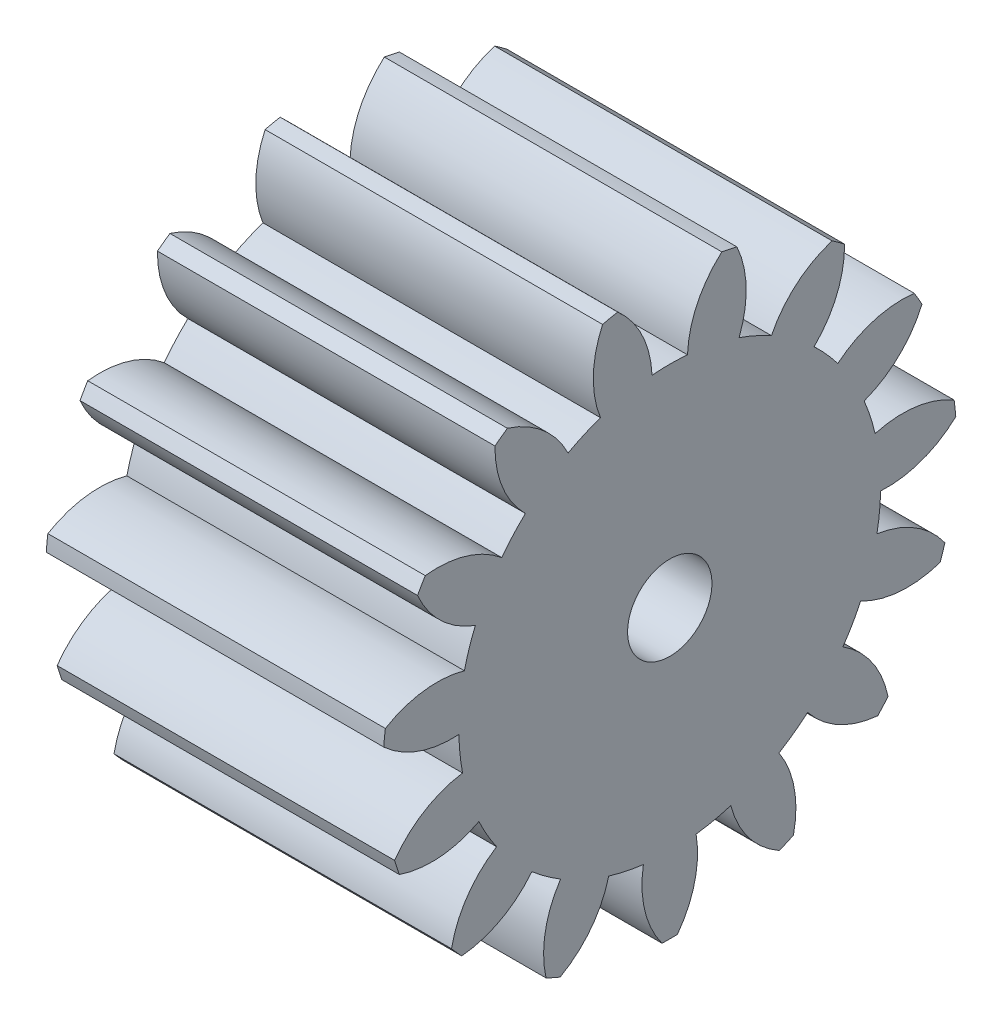
SolidWorks part; units mm, degrees
ref_plane "Plane1" through (0, 0, 0) normal (0, 0, 1) x (1, 0, 0)
ref_plane "Plane2" through (0, 0, 0) normal (0, 1, 0) x (1, 0, 0)
ref_plane "Plane3" through (0, 0, 0) normal (1, 0, 0) x (0, 0, -1)
sketch "HoldingSke" plane through (0, 0, 0) normal (0, 1, 0) x (1, 0, 0)
  line L0 (0, 0) -> (0.483, -0.1294)
  line L1 (-15, 0) -> (100, 0) construction
  line L2 (0, 0) -> (-2.1039, 2.3779)
  line L3 (0, 0) -> (-11.863, 4.5341)
  line L4 (0, 0) -> (8.3417, 2.2352)
  line L5 (0, 0) -> (-46.8476, -17.4728)
  line L6 (0, 0) -> (-16.5793, -11.1861)
  line L7 (-2.1039, 2.3779) -> (8.6586, 51.2059)
  line L8 (-76.2, 54.61) -> (-75.3, 54.61)
  line L9 (-71.009, 38.7566) -> (-53.1078, 45.2721)
  line L10 (-76.2, 71.12) -> (104.1128, 71.12)
  line L11 (0, 0) -> (-20, 0)
  line L12 (-76.2, 101.6) -> (-76.133, 101.6)
  line L13 (24.9733, 27.94) -> (52.9518, 28.4284)
  line L14 (24.9733, 27.94) -> (24.9743, 27.94)
  line L15 (24.9733, 27.94) -> (100.4006, 29.5858)
  line L16 (-63.627, -2) -> (-12.827, -2)
  circle A0 centre (0, 0) radius 2.5
  circle A1 centre (0, 0) radius 12.499
  circle A2 centre (0, 0) radius 37.5
  circle A3 centre (0, 0) radius 2.5
  dimension "MHD" = 24.998
  dimension "Hub_dia" = 75
  dimension "Bore" = 5
  dimension "MBD" = 5
  dimension "Num_teeth" = 15
  dimension "Pitch" = 0.5
  dimension "Overall_len" = 50
  dimension "Show_teeth" = 15
  dimension "Thickness" = 20
  dimension "OAL" = 50.0001
  dimension "T_dim" = 0.9
  dimension "Ap" = 20
  dimension "H" = 19.05
  dimension "Pitch_radius" = 180.3128
  dimension "Width" = 20
  dimension "Backlash" = 0.067
  dimension "Addendum_fac" = 1
  dimension "Dedendum_fac" = 1.25
  dimension "Clearance_fac" = 0.25
  dimension "Dedendum_add" = 0.001
  dimension "Module" = 2
sketch "BasProSke" plane through (0, 0, 0) normal (0, 1, 0) x (1, 0, 0)
  line L0 (-10, 0) -> (60, 0) construction
  line L1 (0, 0) -> (0, 17)
  line L2 (0, 0) -> (20, 0)
  line L3 (20, 0) -> (20, 17)
  line L4 (20, 17) -> (0, 17)
  dimension "Thickness" = 20
  dimension "Diameter" = 34
revolve "Base-Revolve" add sketch "BasProSke" angle 360 about L0
sketch "TooCutSke" plane through (0, 0, 0) normal (1, 0, 0) x (0, 0, -1)
  line L1 (0, 0) -> (0, 107) construction
  line L2 (0, 0) -> (-1.6851, 14.905) construction
  line L3 (0, 0) -> (-6.2081, 29.2069) construction
  line L4 (-1.6851, 14.905) -> (-3.1041, 14.6034) construction
  arc A0 (1.0501, 12.4548) -> (-1.0501, 12.4548) centre (0, 0) ccw
  arc A1 (3.1109, 16.7388) -> (-3.1109, 16.7388) centre (0, 0) ccw
  circle A2 centre (0, 0) radius 15 construction
  circle A3 centre (0, 0) radius 14.0954 construction
  arc A4 (-1.0501, 12.4548) -> (-3.1109, 16.7388) centre (-7.045, 12.2085) ccw
  arc A5 (3.1109, 16.7388) -> (1.0501, 12.4548) centre (7.045, 12.2085) ccw
  dimension "Root_dia" = 24.998
  dimension "Overcut_dia" = 34.0508
  dimension "Pitch_dia" = 30
  dimension "Base_dia" = 28.1908
  dimension "Flank_rad" = 6
  dimension "Half_ang" = 12
  dimension "Half_CT" = 1.4507
extrude "ToothCut" cut sketch "TooCutSke" along normal through all
fillet "Breaks" [suppressed] radius 0.04
fillet "RootFillets" [suppressed] radius 0.501
pattern_circular "TeethCuts" count 15 every 24 about axis through (-10, 0, 0) along (1, 0, 0) of "ToothCut", "RootFillets", "Breaks"
sketch "HubNeaOneSke" plane through (0, 0, 0) normal (-1, 0, 0) x (0, 0, 1)
  circle A0 centre (0, 0) radius 12.499
  dimension "Diameter" = 24.998
extrude "HubNearOne" [suppressed] add sketch "HubNeaOneSke" along normal blind 30.0001
sketch "HubNeaBotSke" plane through (0, 0, 0) normal (-1, 0, 0) x (0, 0, 1)
  circle A0 centre (0, 0) radius 12.499
  dimension "Diameter" = 24.998
extrude "HubNearBoth" [suppressed] add sketch "HubNeaBotSke" along normal blind 15
ref_plane "FarPln" through (20, 0, 0) normal (1, 0, 0) x (0, 0, -1)
sketch "HubFarSke" plane through (20, 0, 0) normal (1, 0, 0) x (0, 0, -1)
  circle A0 centre (0, 0) radius 12.499
  dimension "Diameter" = 24.998
extrude "HubFar" [suppressed] add sketch "HubFarSke" along normal blind 15
sketch "BorSke" plane through (0, 0, 0) normal (1, 0, 0) x (0, 0, -1)
  circle A0 centre (0, 0) radius 2.5
  dimension "Diameter" = 5
extrude "Bore" cut sketch "BorSke" along normal mid plane 100.0001
sketch "KeySke" plane through (0, 0, 0) normal (1, 0, 0) x (0, 0, -1)
  line L0 (-1, 0) -> (-1, 3.4)
  line L1 (-1, 3.4) -> (1, 3.4)
  line L2 (1, 3.4) -> (1, 0)
  line L3 (0, 0) -> (0, 34) construction
  line L4 (-1, 0) -> (1, 0)
  dimension "Offset" = 3.4
extrude "Keyway" [suppressed] cut sketch "KeySke" along normal mid plane 100.0001
pattern_circular "Keyway2" [suppressed] count 2 every 90 about axis through (-10, 0, 0) along (1, 0, 0)
equation "' \"Module@HoldingSke\" = 6.35"
equation "' \"Num_teeth@HoldingSke\" = 12"
equation "' \"Ap@HoldingSke\" =  20"
equation "' \"Ap@HoldingSke\" = 20"
equation "' \"Width@HoldingSke\" = 0.5 * 25.4"
equation "' \"Hub_dia@HoldingSke\"= 1 * 25.4"
equation "' \"Hub_dia@HoldingSke\" = 1 * 25.4"
equation "' \"Overall_len@HoldingSke\" = 1.0 * 25.4"
equation "' \"Bore@HoldingSke\" = 0.75 * 25.4"
equation "' \"T_dim@HoldingSke\" = 0.1 * 25.4"
equation "' \"Width@KeySke\" = 0.25 * 25.4"
equation "' \"Show_teeth@HoldingSke\" = 13"
equation "' \"Backlash@HoldingSke\" = 0.009 * 25.4"
equation "' \"Addendum_fac@HoldingSke\" = 1.0"
equation "' \"Dedendum_fac@HoldingSke\" = 1.25"
equation "' \"Dedendum_add@HoldingSke\" = 0.00005 * 25.4"
equation "' \"Clearance_fac@HoldingSke\" = 0.25"
equation "\"Pitch@HoldingSke\" = 1 / \"Module@HoldingSke\""
equation "\"Overcut_dia@TooCutSke\" = (\"Num_teeth@HoldingSke\" + 2 * \"Addendum_fac@HoldingSke\") / \"Pitch@HoldingSke\" + 0.002 * 25.4"
equation "\"Pitch_dia@TooCutSke\" = \"Num_teeth@HoldingSke\" / \"Pitch@HoldingSke\""
equation "\"Base_dia@TooCutSke\" = \"Num_teeth@HoldingSke\" / \"Pitch@HoldingSke\" * cos((\"Ap@HoldingSke\"  * 3.14159265 / 180))"
equation "\"Root_dia@TooCutSke\" = (\"Num_teeth@HoldingSke\" + 2) / \"Pitch@HoldingSke\" - 2 * (\"Addendum_fac@HoldingSke\" + \"Dedendum_fac@HoldingSke\") / \"Pitch@HoldingSke\" - \"Dedendum_add@HoldingSke\" * 2"
equation "\"Half_ang@TooCutSke\" = 180 / \"Num_teeth@HoldingSke\""
equation "\"Half_CT@TooCutSke\" = \"Num_teeth@HoldingSke\" / \"Pitch@HoldingSke\" * sin((3.14159265 / 2 / \"Num_teeth@HoldingSke\")) / 2 - 7 * \"Backlash@HoldingSke\" / 4"
equation "\"Flank_rad@TooCutSke\" = \"Num_teeth@HoldingSke\" / \"Pitch@HoldingSke\" / 5"
equation "\"Radius@RootFillets\" = \"Clearance_fac@HoldingSke\" / \"Pitch@HoldingSke\" + \"Dedendum_add@HoldingSke\""
equation "\"Break_rad@Breaks\" = 0.02 / \"Pitch@HoldingSke\""
equation "\"Thickness@HoldingSke\" = \"Width@HoldingSke\""
equation "\"OAL@HoldingSke\" = \"Thickness@HoldingSke\""
equation "\"MHD@HoldingSke\" = (\"Num_teeth@HoldingSke\" + 2) / \"Pitch@HoldingSke\" - 2 * (\"Addendum_fac@HoldingSke\" + \"Dedendum_fac@HoldingSke\")  / \"Pitch@HoldingSke\" - \"Dedendum_add@HoldingSke\" * 2"
equation "\"MBD@HoldingSke\" = (\"Num_teeth@HoldingSke\" + 2) / \"Pitch@HoldingSke\" - 2 * (\"Addendum_fac@HoldingSke\" + \"Dedendum_fac@HoldingSke\")  / \"Pitch@HoldingSke\" - \"Dedendum_add@HoldingSke\" * 2 - 0.002 * 25.4"
equation "\"MHD@HoldingSke\" = ((sgn( \"MHD@HoldingSke\" - \"Hub_dia@HoldingSke\" )-1)*( \"MHD@HoldingSke\" - \"Hub_dia@HoldingSke\" ))/-2+ \"Hub_dia@HoldingSke\""
equation "\"MBD@HoldingSke\" = ((sgn( \"MBD@HoldingSke\" - \"Bore@HoldingSke\" )-1)*( \"MBD@HoldingSke\" - \"Bore@HoldingSke\" ))/-2+ \"Bore@HoldingSke\""
equation "\"OAL@HoldingSke\" = ((sgn( \"OAL@HoldingSke\" - \"Overall_len@HoldingSke\" )+1)*( \"OAL@HoldingSke\" - \"Overall_len@HoldingSke\" ))/2 + \"Overall_len@HoldingSke\" + 0.000002 * 25.4"
equation "\"Num_teeth@TeethCuts\" = int( \"Show_teeth@HoldingSke\" ) + 1"
equation "\"Num_teeth@TeethCuts\" = ((sgn( \"Num_teeth@TeethCuts\" - \"Num_teeth@HoldingSke\" )-1)*( \"Num_teeth@TeethCuts\" - \"Num_teeth@HoldingSke\" ))/-2+ \"Num_teeth@HoldingSke\""
equation "\"Num_teeth@TeethCuts\" = ((sgn( \"Num_teeth@TeethCuts\" - 2.0)+1)*( \"Num_teeth@TeethCuts\" - 2.0))/2 +2.0"
equation "\"Angle@TeethCuts\" = 360.0 / \"Num_teeth@HoldingSke\""
equation "\"Diameter@BasProSke\" = (\"Num_teeth@HoldingSke\" + 2 * \"Addendum_fac@HoldingSke\") / \"Pitch@HoldingSke\""
equation "\"Thickness@BasProSke\"  = \"Thickness@HoldingSke\""
equation "' \"Fillet_rad@BasProSke\" =  \"Thickness@HoldingSke\" * 0.05"
equation "' \"Fillet_rad@BasProSke\" = \"Thickness@HoldingSke\" * 0.05"
equation "\"MHD@HoldingSke\" = ((sgn( \"MHD@HoldingSke\" - \"Root_dia@TooCutSke\" )-1)*( \"MHD@HoldingSke\" - \"Root_dia@TooCutSke\" ))/-2+ \"Root_dia@TooCutSke\""
equation "\"Diameter@HubNeaOneSke\" = \"MHD@HoldingSke\""
equation "\"Length@HubNearOne\" = \"OAL@HoldingSke\" - \"Thickness@BasProSke\""
equation "\"Diameter@HubNeaBotSke\" = \"MHD@HoldingSke\""
equation "\"Length@HubNearBoth\" = ( \"OAL@HoldingSke\" - \"Thickness@BasProSke\" ) / 2.0"
equation "\"Thickness@FarPln\" = \"Thickness@BasProSke\""
equation "\"Diameter@HubFarSke\" = \"MHD@HoldingSke\""
equation "\"Length@HubFar\" = ( \"OAL@HoldingSke\" - \"Thickness@BasProSke\" ) / 2.0"
equation "\"Diameter@BorSke\" = \"MBD@HoldingSke\""
equation "\"D1@Bore\" = \"OAL@HoldingSke\" * 2.0"
equation "\"D1@Keyway\" = \"OAL@HoldingSke\" * 2.0"
equation "\"Offset@KeySke\" = \"T_dim@HoldingSke\" + \"MBD@HoldingSke\" / 2.0"
